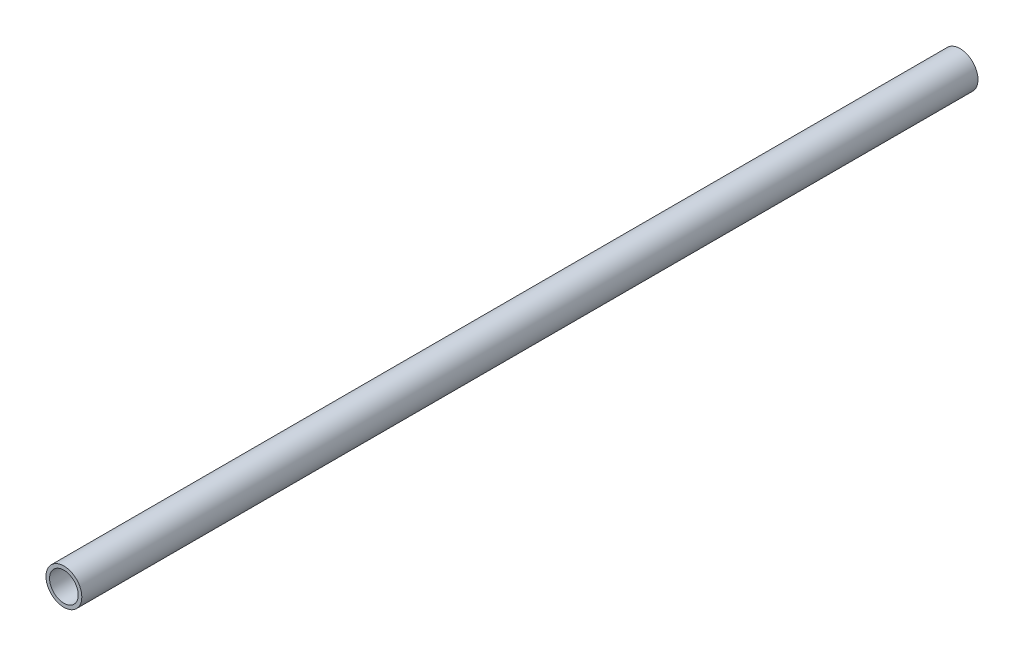
SolidWorks part; units mm, degrees
ref_plane "Front Plane" through (0, 0, 0) normal (0, 0, 1) x (1, 0, 0)
ref_plane "Top Plane" through (0, 0, 0) normal (0, 1, 0) x (1, 0, 0)
ref_plane "Right Plane" through (0, 0, 0) normal (1, 0, 0) x (0, 0, -1)
sketch "Sketch1" plane through (0, 0, 0) normal (0, 0, 1) x (1, 0, 0)
  circle A0 centre (0, 0) radius 5
  circle A1 centre (0, 0) radius 4
  dimension "D1" = 10
  dimension "D2" = 8
extrude "Boss-Extrude1" add sketch "Sketch1" along normal blind 250
